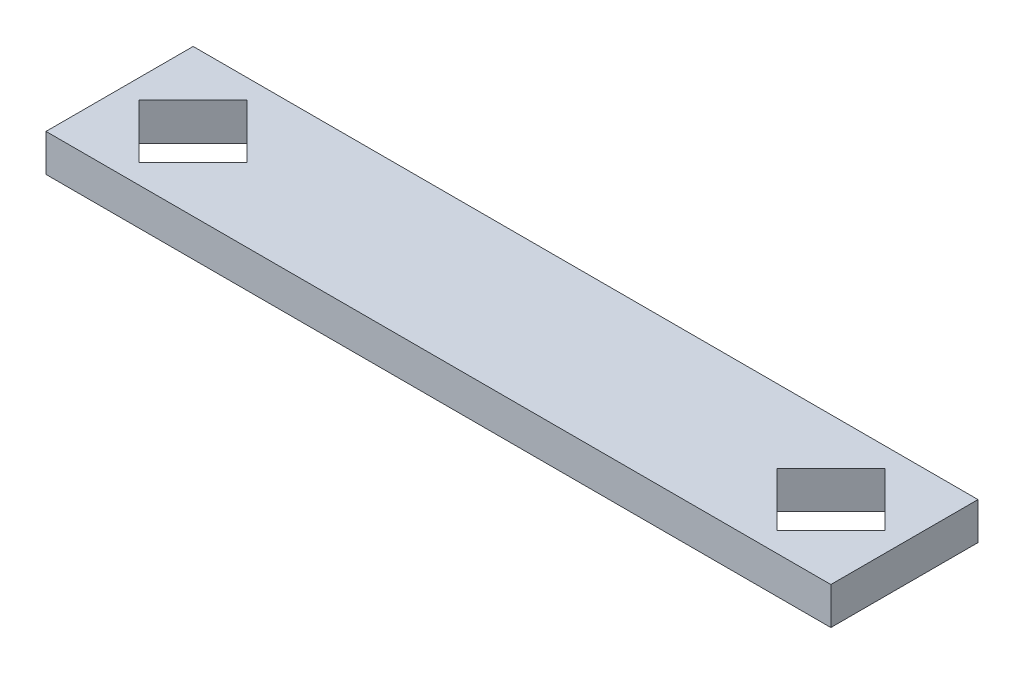
SolidWorks part; units mm, degrees
ref_plane "Front Plane" through (0, 0, 0) normal (0, 0, 1) x (1, 0, 0)
ref_plane "Top Plane" through (0, 0, 0) normal (0, 1, 0) x (1, 0, 0)
ref_plane "Right Plane" through (0, 0, 0) normal (1, 0, 0) x (0, 0, -1)
sketch "Sketch1" plane through (0, 0, 0) normal (0, 1, 0) x (1, 0, 0)
  line L0 (-38, 0) -> (-32.5, -5.5)
  line L1 (-40, -7.5) -> (40, -7.5)
  line L2 (-40, -7.5) -> (-40, 7.5)
  line L3 (-40, 7.5) -> (40, 7.5)
  line L4 (40, -7.5) -> (40, 7.5)
  line L5 (-40, -7.5) -> (40, 7.5) construction
  line L6 (-40, 7.5) -> (40, -7.5) construction
  line L7 (-38, 0) -> (-32.5, 5.5)
  line L8 (-32.5, -5.5) -> (-27, 0)
  line L9 (-32.5, 5.5) -> (-27, 0)
  line L10 (-38, 0) -> (-27, 0) construction
  line L11 (-32.5, -5.5) -> (-32.5, 5.5) construction
  line L12 (-38, 0) -> (-40, 0) construction
  line L13 (-32.5, 5.5) -> (-32.5, 7.5) construction
  line L14 (-32.5, -5.5) -> (-32.5, -7.5) construction
  line L15 (0, -7.5) -> (0, 7.5) construction
  line L16 (32.5, -5.5) -> (32.5, 5.5) construction
  line L17 (38, 0) -> (27, 0) construction
  line L18 (32.5, 5.5) -> (27, 0)
  line L19 (32.5, -5.5) -> (27, 0)
  line L20 (38, 0) -> (32.5, 5.5)
  line L21 (38, 0) -> (32.5, -5.5)
  point P0 (0, 0)
  point P7 (-32.5, 0)
  point P20 (32.5, 0)
  dimension "D1" = 80
  dimension "D2" = 15
  dimension "D3" = 2
extrude "Boss-Extrude1" add sketch "Sketch1" along normal blind 3.8
equation "\"D1@Boss-Extrude1\"=4mm-.2"
